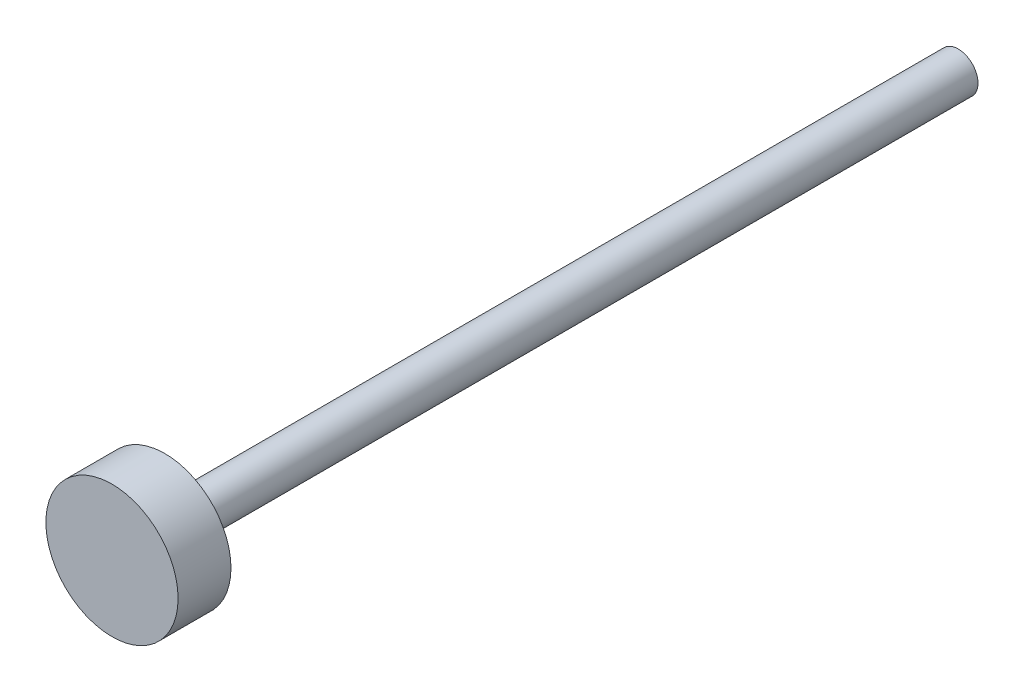
SolidWorks part; units mm, degrees
ref_plane "前视基准面" through (0, 0, 0) normal (0, 0, 1) x (1, 0, 0)
ref_plane "上视基准面" through (0, 0, 0) normal (0, 1, 0) x (1, 0, 0)
ref_plane "右视基准面" through (0, 0, 0) normal (1, 0, 0) x (0, 0, -1)
sketch "草图1" plane through (0, 0, 0) normal (0, 0, 1) x (1, 0, 0)
  circle A0 centre (0, 0) radius 0.75
  dimension "D1" = 1.5
extrude "凸台-拉伸1" add sketch "草图1" along normal blind 30
sketch "草图2" plane through (0, 0, 30) normal (0, 0, 1) x (1, 0, 0)
  circle A0 centre (0, 0) radius 2.5
  dimension "D1" = 5
extrude "凸台-拉伸2" add sketch "草图2" along normal blind 2
